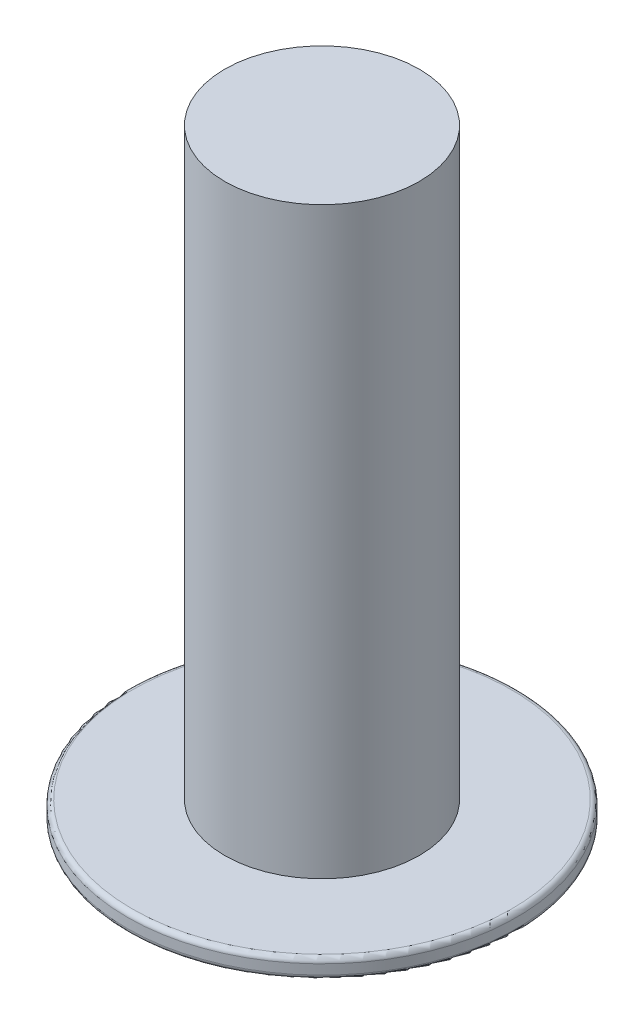
SolidWorks part; units mm, degrees
material "AISI 4140 Steel, quenched & tempered"
ref_plane "Front Plane" through (0, 0, 0) normal (1, 0, 0) x (0, 1, 0)
ref_plane "Top Plane" through (0, 0, 0) normal (0, 0, 1) x (0, 1, 0)
ref_plane "Right Plane" through (0, 0, 0) normal (0, 1, 0) x (-1, 0, 0)
sketch "Sketch1" plane through (0, 0, 0) normal (1, 0, 0) x (0, 1, 0)
  line L0 (-21.912, 0) -> (25.327, 0) construction
  line L1 (0, 30.1451) -> (0, -21.3064) construction
  line L2 (0, 10) -> (60, 10)
  line L3 (60, 10) -> (60, 0)
  line L4 (60, 0) -> (0, 0)
  line L5 (0, 0) -> (0, 10)
  line L7 (0, 20) -> (-2, 20)
  line L8 (-2, 20) -> (-2, 0)
  line L9 (-2, 0) -> (0, 0)
  line L10 (0, 20) -> (0, 10)
  line L11 (-10, 0) -> (-2, 0)
  arc A1 (-2, 15) -> (-10, 0) centre (4.9052, 1.6839) ccw
  dimension "D5" = 8
  dimension "D7" = 15
  dimension "D1" = 20
  dimension "D2" = 60
  dimension "D3" = 2
  dimension "D4" = 40
  dimension "D6" = 30
revolve "Revolve1" add sketch "Sketch1" angle 360 about L0
sketch "Sketch2" plane through (0, -2, 0) normal (0, -1, 0) x (1, 0, 0)
  line L7 (4, -6.9282) -> (8, 0)
  line L8 (8, 0) -> (4, 6.9282)
  line L9 (4, 6.9282) -> (-4, 6.9282)
  line L10 (-4, 6.9282) -> (-8, 0)
  line L11 (-8, 0) -> (-4, -6.9282)
  line L12 (-4, -6.9282) -> (4, -6.9282)
  circle A0 centre (0, 0) radius 8 construction
  dimension "D1" = 8
extrude "Cut-Extrude1" cut sketch "Sketch2" along normal blind 10 from offset 1
fillet "Fillet1" radius 0.5 20 edges at (0, 0, -20) (0, -2, -20) (0, -3, -6.9282) (0, -3, 6.9282) (0.4533, -9.1427, 6.9282) (-0.4533, -9.1427, -6.9282) (6, -3, -3.4641) (6, -3, 3.4641) (-6, -3, 3.4641) (-6, -3, -3.4641) (-4, -5.8501, -6.9282) (-4, -5.8501, 6.9282) (4, -5.8501, 6.9282) (8, -5.8501, 0) (4, -5.8501, -6.9282) (-5.0295, -9.0457, -5.145) (-6.9705, -9.0457, 1.7832) (5.0295, -9.0457, 5.145) (6.9705, -9.0457, -1.7832) (-8, -5.8501, 0)
